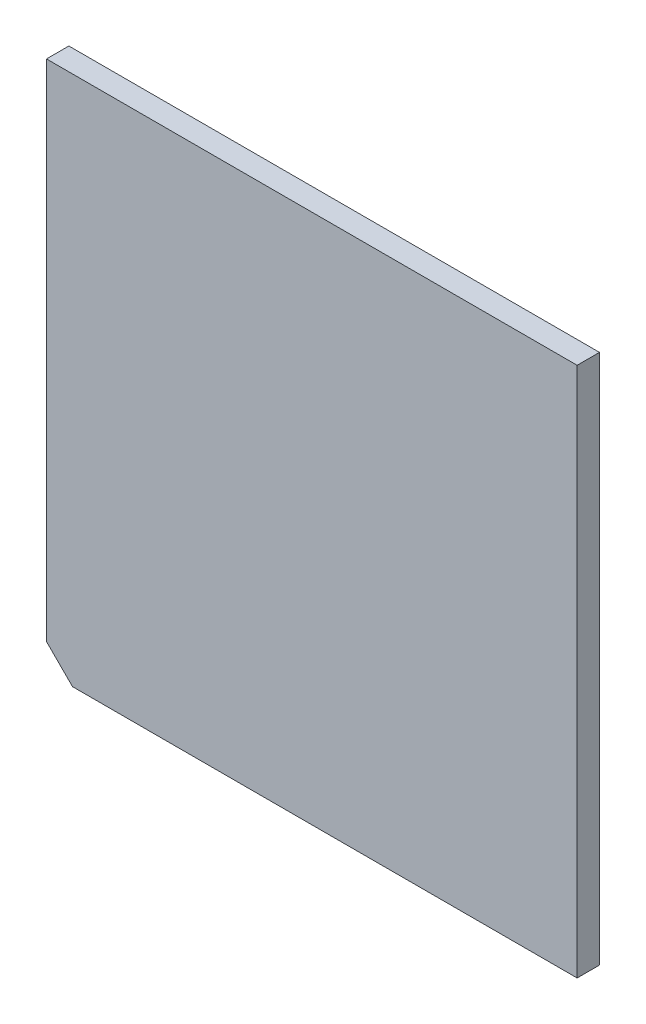
SolidWorks part; units mm, degrees
ref_plane "前视基准面" through (0, 0, 0) normal (0, 0, 1) x (1, 0, 0)
ref_plane "上视基准面" through (0, 0, 0) normal (0, 1, 0) x (1, 0, 0)
ref_plane "右视基准面" through (0, 0, 0) normal (1, 0, 0) x (0, 0, -1)
sketch "草图1" plane through (0, 0, 0) normal (0, 0, 1) x (1, 0, 0)
  line L1 (-51, 51) -> (51, 51)
  line L2 (-51, 51) -> (-51, -51)
  line L3 (-51, -51) -> (51, -51)
  line L4 (51, 51) -> (51, -51)
  line L5 (-51, 51) -> (51, -51) construction
  line L6 (-51, -51) -> (51, 51) construction
  point P0 (0, 0)
  dimension "D1" = 102
  dimension "D2" = 102
extrude "凸台-拉伸1" add sketch "草图1" along normal blind 4.3
chamfer "倒角1" distance 5 1 edges at (-51, -51, 2.15)
